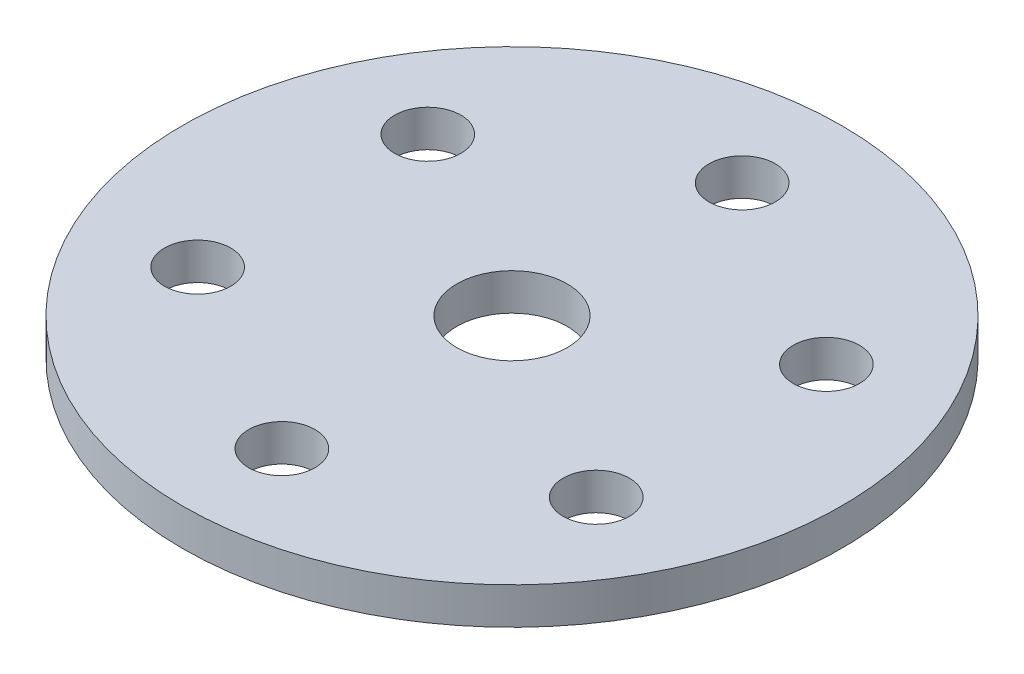
SolidWorks part; units mm, degrees
ref_plane "Front Plane" through (0, 0, 0) normal (0, 0, 1) x (1, 0, 0)
ref_plane "Top Plane" through (0, 0, 0) normal (0, 1, 0) x (1, 0, 0)
ref_plane "Right Plane" through (0, 0, 0) normal (1, 0, 0) x (0, 0, -1)
sketch "Sketch1" plane through (0, 0, 0) normal (0, 1, 0) x (1, 0, 0)
  circle A0 centre (0, 0) radius 17.9
  circle A1 centre (0, 0) radius 3
  dimension "D1" = 35.8
  dimension "D2" = 6
extrude "Boss-Extrude1" add sketch "Sketch1" along normal blind 2
sketch "Sketch2" plane through (0, 2, 0) normal (0, 1, 0) x (1, 0, 0)
  circle A0 centre (0, 0) radius 12.5 construction
  point P2 (0, 12.5)
  point P3 (10.8253, 6.25)
  point P4 (14.1162, 7.6243)
  point P5 (0, 0)
  point P6 (10.8253, -6.25)
  point P7 (0, -12.5)
  point P8 (-10.8253, -6.25)
  point P9 (-10.8253, 6.25)
  point P11 (0, 0)
  point P12 (0, 0)
  dimension "D1" = 25
  dimension "D2" = 6
hole_wizard "M3 Clearance Hole1" positions "Sketch3" profile "Sketch4" hole size "M3" standard "ISO" end condition through all
sketch "Sketch3" plane through (0, 2, 0) normal (0, 1, 0) x (1, 0, 0)
  point P0 (0, 12.5)
  point P3 (-10.8253, 6.25)
  point P6 (-10.8253, -6.25)
  point P9 (0, -12.5)
  point P12 (10.8253, -6.25)
  point P15 (10.8253, 6.25)
sketch "Sketch4" plane through (0, 2, -12.5) normal (1, 0, 0) x (0, 0, 1)
  line L0 (0, 0) -> (0, 2)
  line L1 (0, 2) -> (1.8, 2)
  line L2 (1.8, 2) -> (1.8, 0)
  line L5 (1.8, 0) -> (0, 0)
  line L11 (0, -6.35) -> (0, 107.95) construction
  dimension "Thru Hole Dia." = 3.6
  dimension "Thru Hole Depth" = 2
